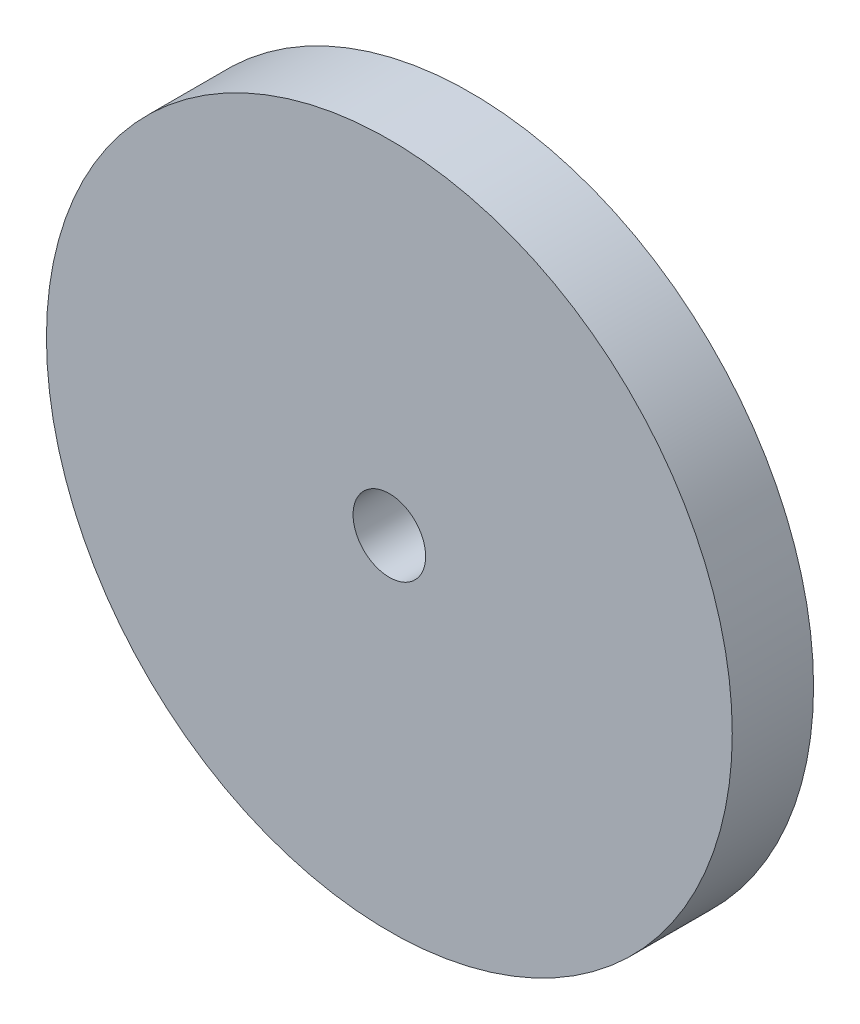
SolidWorks part; units mm, degrees
ref_plane "Front" through (0, 0, 0) normal (0, 0, 1) x (1, 0, 0)
ref_plane "Top" through (0, 0, 0) normal (0, 1, 0) x (1, 0, 0)
ref_plane "Right" through (0, 0, 0) normal (1, 0, 0) x (0, 0, -1)
sketch "Sketch1" plane through (0, 0, 0) normal (0, 0, 1) x (1, 0, 0)
  circle A0 centre (0, 0) radius 30
  dimension "D1" = 60
extrude "Boss-Extrude1" add sketch "Sketch1" along normal mid plane 7.112
sketch "Sketch2" plane through (0, 0, 3.556) normal (0, 0, 1) x (1, 0, 0)
  point P0 (0, 0)
hole_wizard "1/4 (0.25) Diameter Hole1" positions "Sketch3" profile "Sketch4" hole size "1/4" standard "ANSI Inch" end condition through all
sketch "Sketch3" plane through (0, 0, 3.556) normal (0, 0, 1) x (1, 0, 0)
  point P0 (0, 0)
sketch "Sketch4" plane through (0, 0, 3.556) normal (1, 0, 0) x (0, -1, 0)
  line L0 (0, 0) -> (0, 7.112)
  line L1 (0, 7.112) -> (3.175, 7.112)
  line L2 (3.175, 7.112) -> (3.175, 0)
  line L5 (3.175, 0) -> (0, 0)
  line L11 (0, -6.35) -> (0, 107.95) construction
  dimension "Thru Hole Dia." = 6.35
  dimension "Thru Hole Depth" = 7.112
